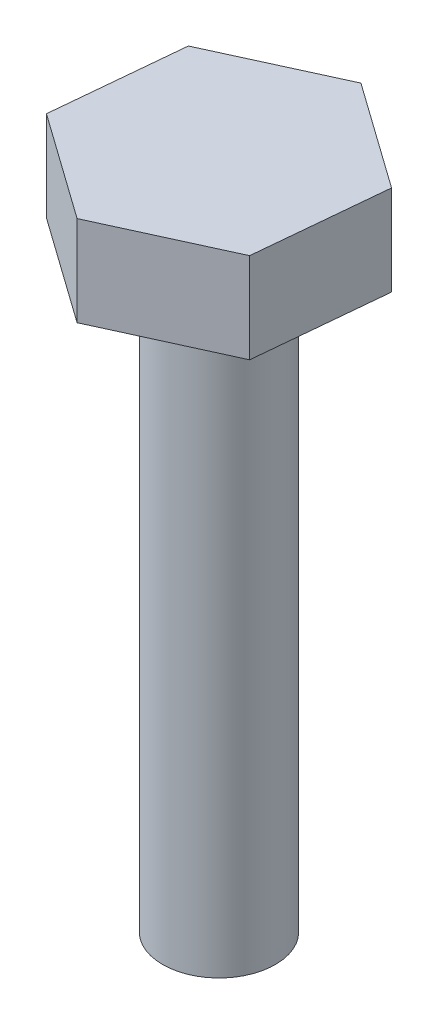
SolidWorks part; units mm, degrees
ref_plane "Front Plane" through (0, 0, 0) normal (0, 0, 1) x (1, 0, 0)
ref_plane "Top Plane" through (0, 0, 0) normal (0, 1, 0) x (1, 0, 0)
ref_plane "Right Plane" through (0, 0, 0) normal (1, 0, 0) x (0, 0, -1)
sketch "Sketch1" plane through (0, 0, 0) normal (0, 1, 0) x (1, 0, 0)
  circle A0 centre (0, 0) radius 0.125
  dimension "D1" = 0.25
extrude "Boss-Extrude2" add sketch "Sketch1" along normal blind 1.3
sketch "Sketch3" plane through (0, 1.3, 0) normal (0, 1, 0) x (1, 0, 0)
  line L1 (0.2352, -0.1673) -> (0.2625, 0.1201)
  line L2 (0.2625, 0.1201) -> (0.0273, 0.2874)
  line L3 (0.0273, 0.2874) -> (-0.2352, 0.1673)
  line L4 (-0.2352, 0.1673) -> (-0.2625, -0.1201)
  line L5 (-0.2625, -0.1201) -> (-0.0273, -0.2874)
  line L6 (-0.0273, -0.2874) -> (0.2352, -0.1673)
  circle A0 centre (0, 0) radius 0.25 construction
  dimension "D1" = 0.5
extrude "Boss-Extrude3" add sketch "Sketch3" along normal blind 0.2
